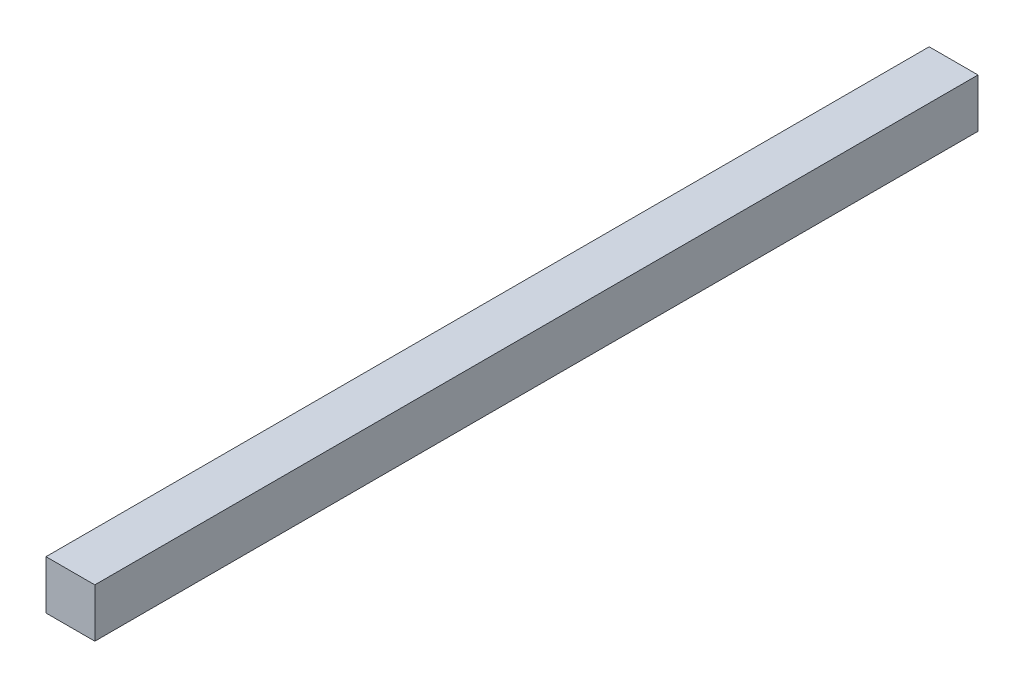
SolidWorks part; units mm, degrees
ref_plane "Front Plane" through (0, 0, 0) normal (0, 0, 1) x (1, 0, 0)
ref_plane "Top Plane" through (0, 0, 0) normal (0, 1, 0) x (1, 0, 0)
ref_plane "Right Plane" through (0, 0, 0) normal (1, 0, 0) x (0, 0, -1)
sketch "Sketch1" plane through (0, 0, 0) normal (0, 0, 1) x (1, 0, 0)
  line L1 (-4.975, 4.975) -> (4.975, 4.975)
  line L2 (-4.975, 4.975) -> (-4.975, -4.975)
  line L3 (-4.975, -4.975) -> (4.975, -4.975)
  line L4 (4.975, 4.975) -> (4.975, -4.975)
  line L5 (-4.975, 4.975) -> (4.975, -4.975) construction
  line L6 (-4.975, -4.975) -> (4.975, 4.975) construction
  point P0 (0, 0)
  point P5 (-4.975, 0)
  dimension "D1" = 9.95
  dimension "D2" = 9.95
extrude "Boss-Extrude1" add sketch "Sketch1" along normal blind 180
